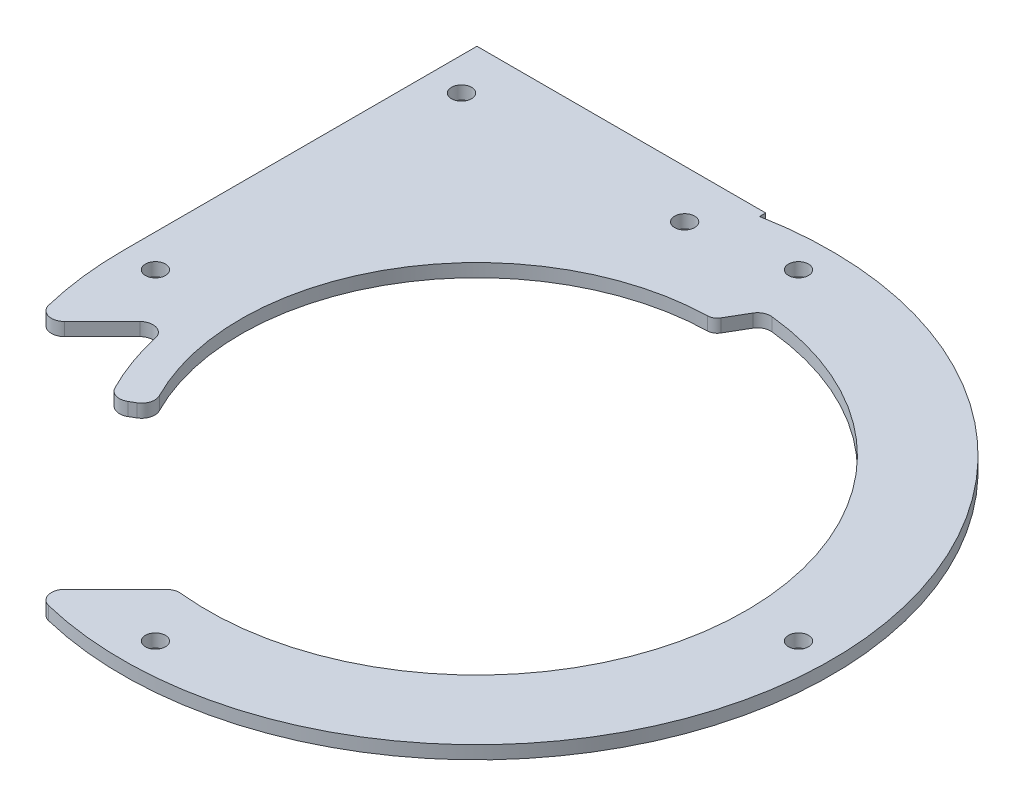
SolidWorks part; units mm, degrees
material "Thornel Mat VMA"
ref_plane "前视基准面" through (0, 0, 0) normal (0, 0, 1) x (1, 0, 0)
ref_plane "上视基准面" through (0, 0, 0) normal (0, 1, 0) x (1, 0, 0)
ref_plane "右视基准面" through (0, 0, 0) normal (1, 0, 0) x (0, 0, -1)
sketch "草图1" plane through (0, 0, 0) normal (0, 1, 0) x (1, 0, 0)
  line L0 (-54, 0) -> (-54, 54)
  line L1 (-54, 54) -> (-10, 54)
  line L2 (-10, 54) -> (-10, 53.066)
  line L3 (-32, 0) -> (-32, 54) construction
  line L4 (-15, 54) -> (-15, 46.6476) construction
  line L5 (-15, 54) -> (-15, 43.7493) construction
  line L6 (-49, 0) -> (-49, 54) construction
  line L7 (-10, 54) -> (-10, 43.7493) construction
  line L8 (-49, 46.6476) -> (-15, 46.6476) construction
  line L9 (-54, 54) -> (-54, 74) construction
  line L10 (-54, 74) -> (-10, 74) construction
  line L11 (-10, 74) -> (-10, 54) construction
  arc A0 (-54, 0) -> (-10, 53.066) centre (0, 0) ccw
  circle A1 centre (0, 0) radius 41
  circle A2 centre (0, 0) radius 32 construction
  circle A4 centre (0, 0) radius 49 construction
  circle A5 centre (-15, 46.6476) radius 1.525
  circle A6 centre (0, 49) radius 1.525
  circle A7 centre (49, 0) radius 1.525
  circle A8 centre (0, -49) radius 1.525
  circle A9 centre (-49, 0) radius 1.525
  circle A20 centre (0, 0) radius 54 construction
  circle A21 centre (-49, 46.6476) radius 1.525
  dimension "D1" = 82
  dimension "D8" = 3.05
  dimension "D4" = 17
  dimension "D2" = 9
  dimension "D3" = 8
  dimension "D5" = 5
  dimension "D6" = 20
  dimension "D7" = 4
extrude "凸台-拉伸1" add sketch "草图1" along normal blind 2
sketch "草图2" plane through (0, 0, 0) normal (0, 1, 0) x (1, 0, 0)
  line L0 (0, 0) -> (-41, 0) construction
  line L1 (-41, 0) -> (-37.47, 0)
  line L2 (0, 0) -> (-49, 0) construction
  line L3 (0, 36) -> (0, 0) construction
  line L4 (0, 0) -> (2.86, 40.9001) construction
  line L5 (0.4283, 36.7338) -> (2.86, 40.9001)
  line L6 (-35.9712, 1.44) -> (0, 0) construction
  arc A0 (-0.8325, 35.9904) -> (-35.9712, 1.44) centre (0, 0) ccw
  arc A1 (2.86, 40.9001) -> (-41, 0) centre (0, 0) ccw
  circle A2 centre (0, 0) radius 41 construction
  arc A6 (-35.9712, 1.44) -> (-37.47, 0) centre (-37.47, 1.5) cw
  arc A7 (-0.8325, 35.9904) -> (0.4283, 36.7338) centre (-0.8672, 37.49) ccw
  dimension "D1" = 72
  dimension "D4" = 1.5
  dimension "D5" = 1.5
  dimension "D6" = 90
  dimension "D7" = 4
extrude "凸台-拉伸3" add sketch "草图2" along normal up to surface (2 mm away) up to face at (-49, 2, 1.525)
fillet "圆角1" radius 2 2 edges at (2.86, 1, -40.9001) (-41, 1, 0)
sketch "草图4" plane through (0, 0, 0) normal (0, -1, 0) x (1, 0, 0)
  line L0 (-38.9487, 0) -> (-37.47, 0) construction
  line L1 (-38.9487, 0) -> (-37.47, 0)
  line L2 (0, 0) -> (-37.47, 0) construction
  line L3 (-31.1769, 18) -> (-35.507, 20.5)
  line L4 (-31.1769, 18) -> (0, 0) construction
  arc A0 (-40.9461, 2.1026) -> (-38.9487, 0) centre (-38.9487, 2) ccw construction
  arc A1 (-35.9712, -1.44) -> (-37.47, 0) centre (-37.47, -1.5) ccw construction
  arc A2 (-40.9461, 2.1026) -> (-38.9487, 0) centre (-38.9487, 2) ccw
  arc A3 (-35.9712, -1.44) -> (-37.47, 0) centre (-37.47, -1.5) ccw
  arc A4 (-31.1769, 18) -> (-35.9712, -1.44) centre (0, 0) ccw
  arc A5 (4.1522, -40.7892) -> (-40.9461, 2.1026) centre (0, 0) ccw construction
  arc A6 (-35.507, 20.5) -> (-40.9461, 2.1026) centre (0, 0) ccw
  dimension "D1" = 30
extrude "凸台-拉伸5" add sketch "草图4" against normal blind 2
sketch "草图5" plane through (0, 0, 0) normal (0, -1, 0) x (1, 0, 0)
  line L0 (0, 0) -> (-38.1838, 38.1838) construction
  line L1 (0, 0) -> (-36, 0) construction
  line L2 (0, 0) -> (-51.5229, 16.1676) construction
  line L3 (0, 0) -> (-16.1676, 51.5229) construction
  line L6 (-16.1676, 51.5229) -> (-5.3006, 40.6559)
  line L7 (-51.5229, 16.1676) -> (-40.6559, 5.3006)
  arc A0 (-31.1769, 18) -> (-0.8325, -35.9904) centre (0, 0) ccw construction
  arc A1 (-10, -53.066) -> (-54, 0) centre (0, 0) ccw construction
  arc A2 (-51.5229, 16.1676) -> (-16.1676, 51.5229) centre (0, 0) cw
  arc A5 (4.1522, -40.7892) -> (-35.507, 20.5) centre (0, 0) ccw construction
  arc A6 (-40.6559, 5.3006) -> (-5.3006, 40.6559) centre (0, 0) cw
  dimension "D1" = 45
  dimension "D2" = 50
extrude "切除-拉伸1" cut sketch "草图5" against normal blind 10
fillet "圆角3" radius 2 6 edges at (-31.1769, 1, 18) (-5.3006, 1, 40.6559) (-35.507, 1, 20.5) (-40.6559, 1, 5.3006) (-51.5229, 1, 16.1676) (-16.1676, 1, 51.5229)
